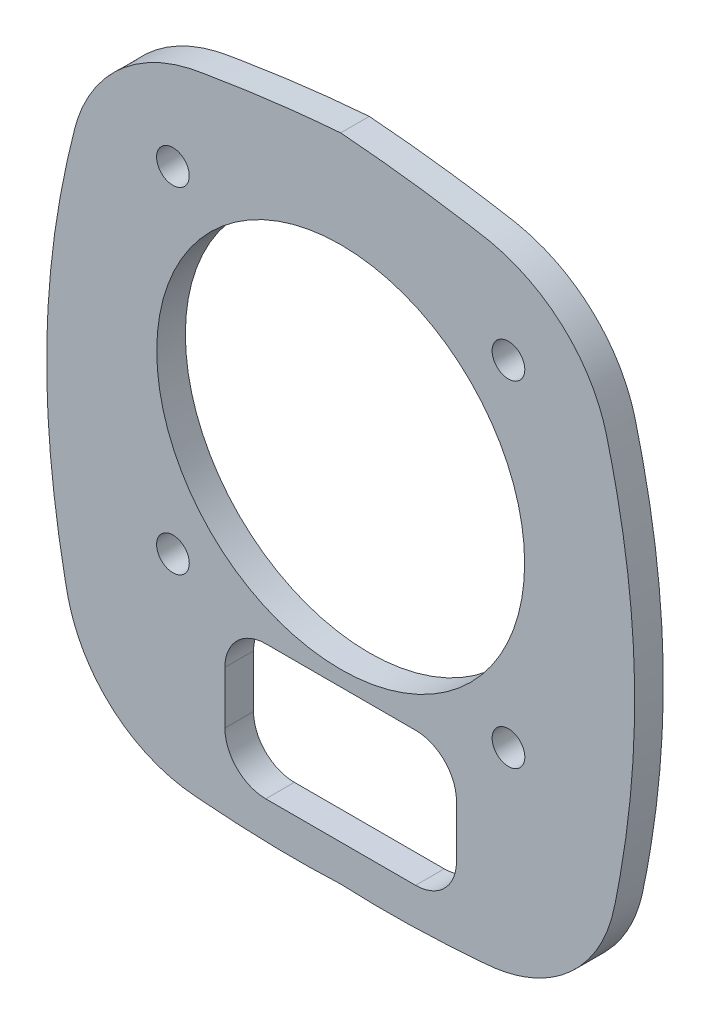
SolidWorks part; units mm, degrees
material "Фанера"
ref_plane "Front Plane" through (0, 0, 0) normal (0, 0, 1) x (1, 0, 0)
ref_plane "Top Plane" through (0, 0, 0) normal (0, 1, 0) x (1, 0, 0)
ref_plane "Right Plane" through (0, 0, 0) normal (1, 0, 0) x (0, 0, -1)
sketch "Эскиз1" plane through (0, 0, 0) normal (0, 0, 1) x (1, 0, 0)
  line L0 (-25.2911, 103.6369) -> (38.3998, 103.6369) construction
  line L1 (0.0004, 137.8459) -> (0.0004, 83.3564) construction
  line L2 (-16.3355, 87.3015) -> (50.6654, 154.3023) construction
  line L4 (-7.3309, 71.0024) -> (7.3317, 71.0024)
  line L5 (-11.3309, 75.0024) -> (-11.3309, 80.1435)
  line L6 (-7.3309, 84.1435) -> (7.3317, 84.1435)
  line L7 (11.3317, 75.0024) -> (11.3317, 80.1435)
  line L8 (-11.3309, 71.0024) -> (11.3317, 84.1435) construction
  line L9 (-11.3309, 84.1435) -> (11.3317, 71.0024) construction
  circle A0 centre (16.4175, 120.0545) radius 1.6
  circle A1 centre (0, 103.6369) radius 5.3081 construction
  circle A2 centre (0, 103.6369) radius 18
  circle A3 centre (-16.4168, 120.0545) radius 1.6
  circle A4 centre (-16.4168, 87.2194) radius 1.6
  circle A5 centre (16.4175, 87.2194) radius 1.6
  arc A6 (7.3317, 84.1435) -> (11.3317, 80.1435) centre (7.3317, 80.1435) cw
  arc A7 (-11.3309, 80.1435) -> (-7.3309, 84.1435) centre (-7.3309, 80.1435) cw
  arc A8 (7.3317, 71.0024) -> (11.3317, 75.0024) centre (7.3317, 75.0024) ccw
  arc A9 (-7.3309, 71.0024) -> (-11.3309, 75.0024) centre (-7.3309, 75.0024) cw
  spline S2 degree 3 poles (0, 131.1062) (-0.3702, 131.0763) (-1.1028, 131.0172) (-2.1891, 130.9196) (-3.4436, 130.7985) (-4.8817, 130.6463) (-6.503, 130.4563) (-8.125, 130.2474) (-9.7417, 130.0206) (-11.3628, 129.775) (-12.676, 129.562) (-13.6897, 129.3901) (-14.4132, 129.2646) (-15.1596, 129.0944) (-15.9282, 128.8804) (-16.7152, 128.6164) (-17.5163, 128.2986) (-18.3267, 127.9229) (-19.728, 127.1697) (-21.748, 125.7276) (-23.5677, 123.7) (-24.6127, 122.0113) (-25.1013, 121.049) (-25.4626, 120.2251) (-25.7389, 119.4608) (-25.9468, 118.7675) (-26.0817, 118.2397) (-26.2129, 117.7174) (-26.5508, 116.3391) (-27.0624, 114.0664) (-27.6532, 110.9226) (-28.1312, 107.7137) (-28.4753, 104.5458) (-28.6991, 101.2935) (-28.8206, 96.9974) (-28.6815, 92.7434) (-28.3105, 88.4657) (-28.0114, 86.0398) (-27.6872, 83.8215) (-27.4469, 82.3517) (-27.1704, 80.8223) (-26.9644, 79.7639) (-26.7959, 78.9056) (-26.6398, 78.2276) (-26.4962, 77.7067) (-26.3157, 77.1264) (-26.0804, 76.4742) (-25.653, 75.4713) (-25.0212, 74.2848) (-23.7978, 72.5158) (-22.2749, 70.9806) (-20.5079, 69.748) (-19.0733, 68.9835) (-17.5657, 68.3965) (-16.3741, 68.0858) (-15.5407, 67.9319) (-15.0588, 67.8587) (-14.5432, 67.7975) (-13.9938, 67.7521) (-13.4123, 67.7047) (-12.6889, 67.6502) (-11.8043, 67.5891) (-10.7388, 67.5241) (-8.9321, 67.4292) (-6.9506, 67.36) (-4.8154, 67.3354) (-3.1864, 67.3427) (-1.5776, 67.3747) (-0.5086, 67.4211) (0, 67.4432) knots 0 0 0 0 0.010771 0.021313 0.031628 0.047323 0.06325 0.078966 0.094746 0.110593 0.126514 0.133325 0.14041 0.147806 0.155515 0.163537 0.171867 0.180498 0.189424 0.217986 0.251993 0.267593 0.275472 0.283275 0.293668 0.299019 0.30426 0.309463 0.314637 0.345412 0.377007 0.407382 0.439473 0.469388 0.501899 0.564079 0.59267 0.626404 0.634941 0.657685 0.669589 0.680012 0.688953 0.694954 0.700182 0.70462 0.712574 0.720276 0.736225 0.751452 0.782552 0.798228 0.813816 0.829575 0.845041 0.849441 0.854152 0.859171 0.864496 0.870136 0.876092 0.885532 0.895852 0.907048 0.937998 0.953339 0.968971 0.985238 1 1 1 1
  spline S3 degree 3 poles (0, 67.4432) (0.2498, 67.4316) (0.7627, 67.4079) (1.5522, 67.3807) (2.3816, 67.3592) (3.4924, 67.3408) (4.8609, 67.3356) (7.0177, 67.3614) (9.2063, 67.4395) (11.3606, 67.5592) (12.7428, 67.6525) (13.8286, 67.7384) (14.6702, 67.8067) (15.4337, 67.9108) (16.4372, 68.0976) (17.7023, 68.4416) (19.1991, 69.0422) (20.6198, 69.8178) (22.3705, 71.0635) (23.8791, 72.6123) (25.088, 74.3955) (25.7081, 75.5866) (26.1255, 76.5907) (26.3812, 77.3194) (26.6103, 78.0983) (26.7713, 78.7963) (26.904, 79.4609) (27.0194, 80.041) (27.1412, 80.6774) (27.2695, 81.37) (27.4848, 82.582) (27.6985, 83.8954) (28.021, 86.1095) (28.3221, 88.5758) (28.6884, 92.8624) (28.8217, 97.1322) (28.6919, 101.4443) (28.4611, 104.7035) (28.1104, 107.8744) (27.6255, 111.0861) (27.0271, 114.2367) (26.4904, 116.6008) (26.103, 118.158) (25.9212, 118.8668) (25.6776, 119.6395) (25.1101, 121.1479) (23.8327, 123.4328) (21.623, 125.8387) (19.5853, 127.2596) (18.1767, 127.9969) (17.3651, 128.3626) (16.5634, 128.671) (15.7765, 128.926) (15.0085, 129.1319) (14.2626, 129.2936) (13.5403, 129.415) (12.5345, 129.5857) (11.2349, 129.7948) (9.1036, 130.1162) (6.9662, 130.4026) (4.8289, 130.6521) (3.2288, 130.8207) (1.6218, 130.9738) (0.5464, 131.0616) (0, 131.1062) knots 0 0 0 0 0.007253 0.014889 0.022909 0.031315 0.04711 0.062594 0.093869 0.110611 0.125167 0.134046 0.142201 0.149649 0.156381 0.171796 0.187581 0.203049 0.218623 0.249784 0.265042 0.281007 0.288624 0.296566 0.303391 0.312159 0.31733 0.323048 0.329311 0.33612 0.343475 0.365012 0.374709 0.408363 0.437047 0.499467 0.532106 0.562131 0.594201 0.6246 0.656308 0.687188 0.69489 0.702849 0.708403 0.718376 0.749562 0.783616 0.812211 0.821107 0.82971 0.838012 0.846006 0.85369 0.861061 0.868129 0.874931 0.890648 0.906302 0.937441 0.953185 0.968707 0.984102 1 1 1 1
  spline S4 degree 1 poles (0.0004, 131.9089) (-0.0011, 66.6424) knots 0 0 1 1 construction
  spline S5 degree 1 poles (-0.0011, 66.6424) (0.0004, 131.9089) knots 0 0 1 1 construction
  spline S6 degree 3 poles (0.0004, 131.9089) (-2.1591, 131.7346) (-5.3932, 131.4185) (-9.6929, 130.8482) (-12.3658, 130.4183) (-14.508, 130.0793) (-16.7336, 129.5269) (-19.3432, 128.4151) (-22.1553, 126.4452) (-24.4752, 123.8994) (-25.8878, 121.4202) (-26.6662, 119.256) (-27.1828, 117.1196) (-27.7959, 114.4843) (-28.4047, 111.2734) (-28.8952, 108.0459) (-29.3767, 103.717) (-29.6542, 98.2761) (-29.4905, 92.8306) (-29.1184, 88.4954) (-28.7207, 85.2562) (-28.3032, 82.5756) (-27.909, 80.4309) (-27.6123, 78.849) (-27.207, 77.1816) (-26.3998, 75.0513) (-24.9514, 72.5746) (-22.5477, 70.0835) (-19.6247, 68.246) (-16.9139, 67.3239) (-14.6389, 66.9838) (-12.4813, 66.8357) (-9.773, 66.6563) (-6.5186, 66.5443) (-3.2584, 66.5254) (-1.0865, 66.5953) (-0.0011, 66.6424) knots -0.000628 -0.000628 -0.000628 -0.000628 0.06189 0.093149 0.124407 0.140037 0.155666 0.186925 0.218184 0.249442 0.280701 0.296331 0.31196 0.343219 0.374478 0.405736 0.436995 0.499513 0.56203 0.593289 0.624548 0.655807 0.671436 0.687065 0.702695 0.718324 0.749583 0.780842 0.812101 0.843359 0.858989 0.874618 0.905877 0.937136 0.968394 0.999653 0.999653 0.999653 0.999653 construction
  spline S7 degree 3 poles (-0.0011, 66.6424) (2.1695, 66.5419) (5.4339, 66.5053) (9.772, 66.6566) (12.4817, 66.8357) (14.6377, 66.9839) (16.9129, 67.3235) (19.6236, 68.2456) (22.5465, 70.0825) (24.9503, 72.573) (26.399, 75.0504) (27.2066, 77.1787) (27.611, 78.8488) (27.9094, 80.43) (28.3025, 82.573) (28.7205, 85.2543) (29.1182, 88.4931) (29.4904, 92.8281) (29.6543, 98.2733) (29.3769, 103.7139) (28.8956, 108.0425) (28.4053, 111.2701) (27.7968, 114.4803) (27.1835, 117.1167) (26.6676, 119.2508) (25.8901, 121.4161) (24.4735, 123.9025) (22.1547, 126.4453) (19.3425, 128.4158) (16.7315, 129.5274) (14.5094, 130.0792) (12.3645, 130.4186) (9.6926, 130.8481) (5.3927, 131.4191) (2.1594, 131.7325) (0.0004, 131.9089) knots 0.000347 0.000347 0.000347 0.000347 0.062864 0.094123 0.125382 0.141011 0.156641 0.187899 0.219158 0.250417 0.281676 0.297305 0.312935 0.328564 0.344193 0.375452 0.406711 0.43797 0.500487 0.563005 0.594264 0.625522 0.656781 0.68804 0.703669 0.719299 0.750558 0.781816 0.813075 0.844334 0.859963 0.875593 0.906852 0.93811 1.000628 1.000628 1.000628 1.000628 construction
  point P21 (0.0004, 77.5729)
  dimension "D2" = 36
  dimension "D4" = 3.2
  dimension "D5" = 4
  dimension "D3" = 45
  dimension "D1" = 0.8
extrude "Бобышка-Вытянуть1" add sketch "Эскиз1" along normal mid plane 2.8
